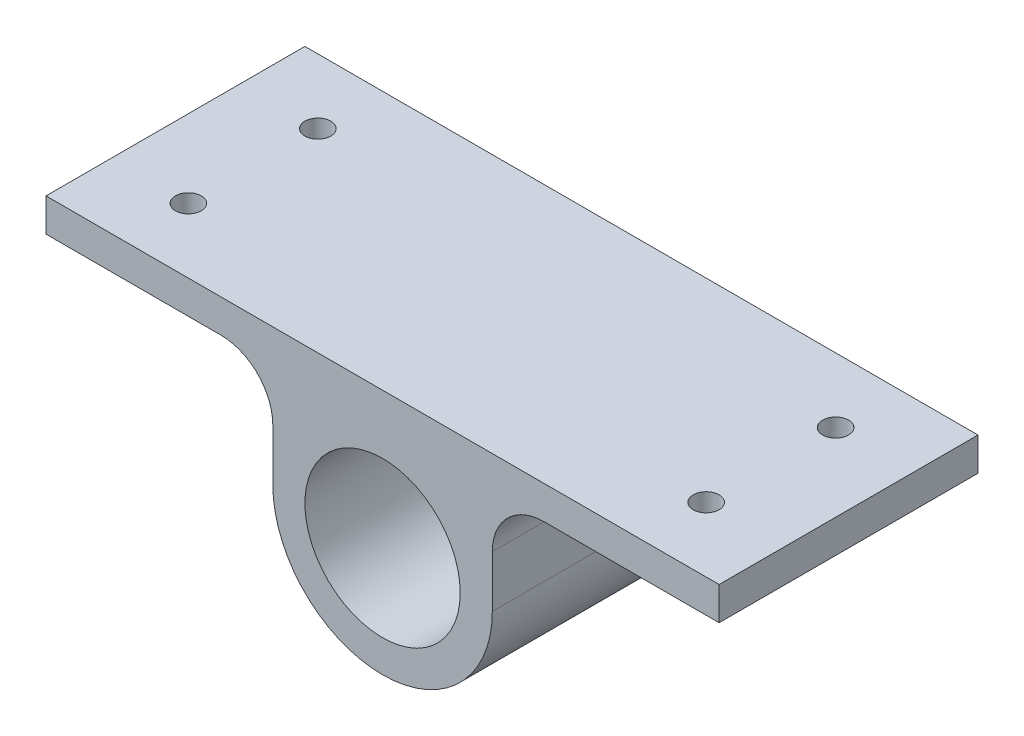
SolidWorks part; units mm, degrees
ref_plane "Front Plane" through (0, 0, 0) normal (0, 0, 1) x (1, 0, 0)
ref_plane "Top Plane" through (0, 0, 0) normal (0, 1, 0) x (1, 0, 0)
ref_plane "Right Plane" through (0, 0, 0) normal (1, 0, 0) x (0, 0, -1)
sketch "Sketch1" plane through (0, 0, 0) normal (0, 0, 1) x (1, 0, 0)
  line L0 (0, 0) -> (650, 0)
  line L1 (650, 0) -> (650, -32)
  line L2 (325, 0) -> (325, -238) construction
  line L3 (431, -132) -> (431, -82)
  line L4 (481, -32) -> (650, -32)
  line L5 (169, -32) -> (0, -32)
  line L6 (0, 0) -> (0, -32)
  line L7 (219, -132) -> (219, -82)
  circle A0 centre (325, -132) radius 75
  arc A1 (219, -132) -> (431, -132) centre (325, -132) ccw
  arc A2 (431, -82) -> (481, -32) centre (481, -82) cw
  arc A3 (169, -32) -> (219, -82) centre (169, -82) cw
  point P5 (-741.8904, 146.8714)
  point P16 (431, -32)
  point P19 (219, -32)
  dimension "D4" = 150
  dimension "D5" = 106
  dimension "D6" = 50
  dimension "D1" = 32
  dimension "D2" = 325
  dimension "D3" = 132
extrude "Boss-Extrude1" add sketch "Sketch1" along normal blind 250
sketch "Sketch2" plane through (0, 0, 0) normal (0, 1, 0) x (1, 0, 0)
  line L0 (325, 0) -> (325, 46.0659)
  line L1 (650, 0) -> (0, 0) construction
  line L2 (650, -250) -> (650, 0) construction
  circle A0 centre (575, -62.5) radius 12.5
  circle A1 centre (575, -187.5) radius 12.5
  circle A2 centre (75, -62.5) radius 12.5
  circle A3 centre (75, -187.5) radius 12.5
  point P8 (0, 0)
  dimension "D3" = 25
  dimension "D1" = 125
  dimension "D2" = 62.5
  dimension "D4" = 75
extrude "Cut-Extrude1" cut sketch "Sketch2" against normal through all contours A2 | A3 | A1 | A0
